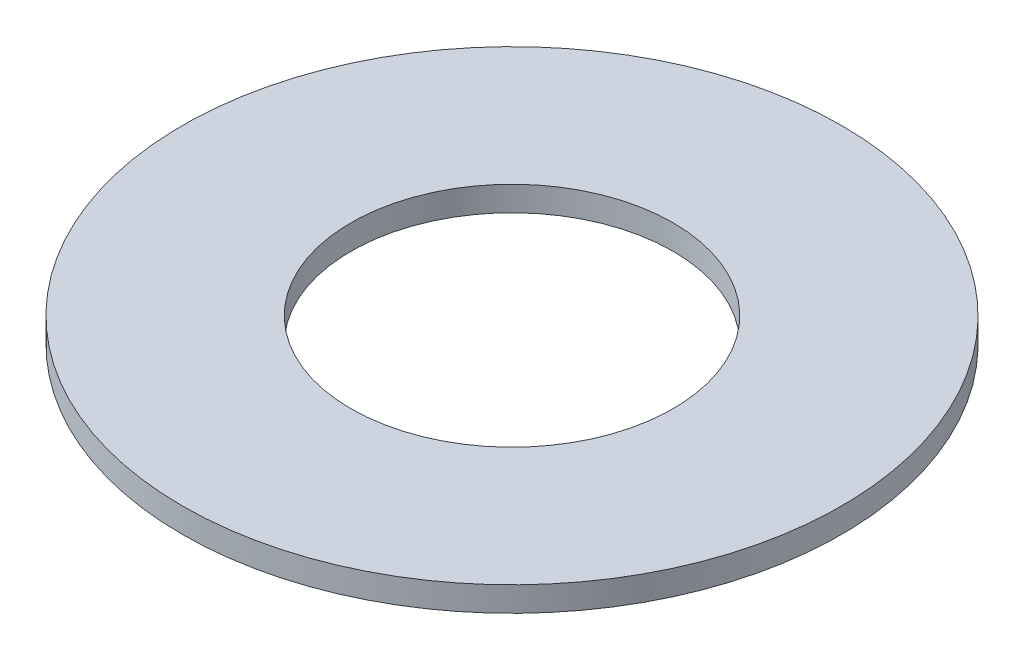
SolidWorks part; units mm, degrees
ref_plane "Front Plane" through (0, 0, 0) normal (0, 0, 1) x (1, 0, 0)
ref_plane "Top Plane" through (0, 0, 0) normal (0, 1, 0) x (1, 0, 0)
ref_plane "Right Plane" through (0, 0, 0) normal (1, 0, 0) x (0, 0, -1)
sketch "Sketch1" plane through (0, 0, 0) normal (0, 1, 0) x (1, 0, 0)
  circle A0 centre (0, 0) radius 60
  dimension "D1" = 120
extrude "Boss-Extrude1" add sketch "Sketch1" along normal blind 4.5
sketch "Sketch2" plane through (0, 4.5, 0) normal (0, 1, 0) x (1, 0, 0)
  circle A0 centre (0, 0) radius 29.325
  dimension "D1" = 58.65
extrude "Cut-Extrude1" cut sketch "Sketch2" against normal through all both and the other way through all
